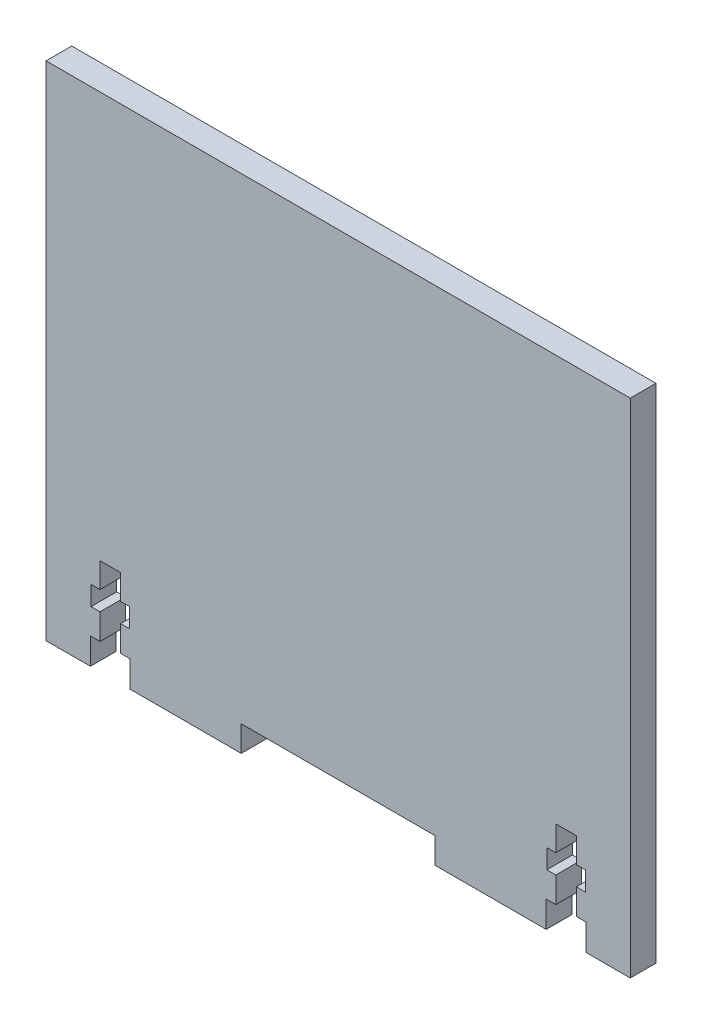
SolidWorks part; units mm, degrees
ref_plane "Front Plane" through (0, 0, 0) normal (0, 0, 1) x (1, 0, 0)
ref_plane "Top Plane" through (0, 0, 0) normal (0, 1, 0) x (1, 0, 0)
ref_plane "Right Plane" through (0, 0, 0) normal (1, 0, 0) x (0, 0, -1)
sketch "Sketch1" plane through (0, 0, 0) normal (0, 0, 1) x (1, 0, 0)
  line L1 (-45.5, 39.115) -> (45.5, 39.115)
  line L2 (-45.5, 39.115) -> (-45.5, -39.115)
  line L3 (-45.5, -39.115) -> (45.5, -39.115)
  line L4 (45.5, 39.115) -> (45.5, -39.115)
  line L5 (-45.5, 39.115) -> (45.5, -39.115) construction
  line L6 (-45.5, -39.115) -> (45.5, 39.115) construction
  point P0 (0, 0)
  dimension "D1" = 91
  dimension "D2" = 78.23
extrude "Boss-Extrude1" add sketch "Sketch1" along normal blind 4
sketch "Sketch2" plane through (0, 0, 4) normal (0, 0, 1) x (1, 0, 0)
  line L0 (38.6, -39.115) -> (38.6, -35.015)
  line L1 (-45.5, -39.115) -> (45.5, -39.115) construction
  line L2 (38.6, -35.015) -> (37.1, -35.015)
  line L3 (37.1, -35.015) -> (37.1, -31.015)
  line L4 (37.1, -31.015) -> (38.5, -31.015)
  line L5 (38.5, -31.015) -> (38.5, -28.015)
  line L6 (38.5, -28.015) -> (37.1, -28.015)
  line L7 (37.1, -28.015) -> (37.1, -24.115)
  line L8 (37.1, -24.115) -> (33.9, -24.115)
  line L9 (35.5, -24.115) -> (35.5, -39.115) construction
  line L10 (45.5, -39.115) -> (45.5, 39.115) construction
  line L11 (33.9, -28.015) -> (33.9, -24.115)
  line L12 (32.5, -28.015) -> (33.9, -28.015)
  line L13 (32.5, -31.015) -> (32.5, -28.015)
  line L14 (33.9, -31.015) -> (32.5, -31.015)
  line L15 (33.9, -35.015) -> (33.9, -31.015)
  line L16 (32.4, -35.015) -> (33.9, -35.015)
  line L17 (32.4, -39.115) -> (32.4, -35.015)
  line L18 (32.4, -39.115) -> (38.6, -39.115)
  line L19 (0, 39.115) -> (0, -39.115) construction
  line L20 (45.5, 39.115) -> (-45.5, 39.115) construction
  line L21 (-35.5, -24.115) -> (-35.5, -39.115) construction
  line L22 (-32.4, -39.115) -> (-38.6, -39.115)
  line L23 (-32.4, -39.115) -> (-32.4, -35.015)
  line L24 (-32.4, -35.015) -> (-33.9, -35.015)
  line L25 (-33.9, -35.015) -> (-33.9, -31.015)
  line L26 (-33.9, -31.015) -> (-32.5, -31.015)
  line L27 (-32.5, -31.015) -> (-32.5, -28.015)
  line L28 (-32.5, -28.015) -> (-33.9, -28.015)
  line L29 (-33.9, -28.015) -> (-33.9, -24.115)
  line L30 (-37.1, -24.115) -> (-33.9, -24.115)
  line L31 (-37.1, -28.015) -> (-37.1, -24.115)
  line L32 (-38.5, -28.015) -> (-37.1, -28.015)
  line L33 (-38.5, -31.015) -> (-38.5, -28.015)
  line L34 (-37.1, -31.015) -> (-38.5, -31.015)
  line L35 (-37.1, -35.015) -> (-37.1, -31.015)
  line L36 (-38.6, -35.015) -> (-37.1, -35.015)
  line L37 (-38.6, -39.115) -> (-38.6, -35.015)
  dimension "D1" = 10
  dimension "D2" = 6.2
  dimension "D3" = 3.2
  dimension "D4" = 6
  dimension "D5" = 3
  dimension "D6" = 4.1
  dimension "D7" = 15
  dimension "D8" = 4
extrude "Cut-Extrude2" cut sketch "Sketch2" against normal through all
sketch "Sketch3" plane through (0, 0, 4) normal (0, 0, 1) x (1, 0, 0)
  line L0 (-32.4, -39.115) -> (32.4, -39.115) construction
  line L1 (-15.1, -39.115) -> (15.1, -39.115)
  line L2 (-15.1, -39.115) -> (-15.1, -35.115)
  line L3 (-15.1, -35.115) -> (15.1, -35.115)
  line L4 (15.1, -39.115) -> (15.1, -35.115)
  line L7 (-15.1, -39.115) -> (-15.1, -35.115)
  line L8 (-15.1, -35.115) -> (-32.4, -35.115)
  line L11 (15.1, -39.115) -> (15.1, -35.115)
  point P7 (0, -39.115)
  point P8 (0, -39.115)
  line M45 (-32.4, -39.115) -> (32.4, -39.115)
  dimension "D1" = 30.2
  dimension "D2" = 4
extrude "Cut-Extrude3" cut sketch "Sketch3" against normal blind 4 contours L4 L3 L2 M45
